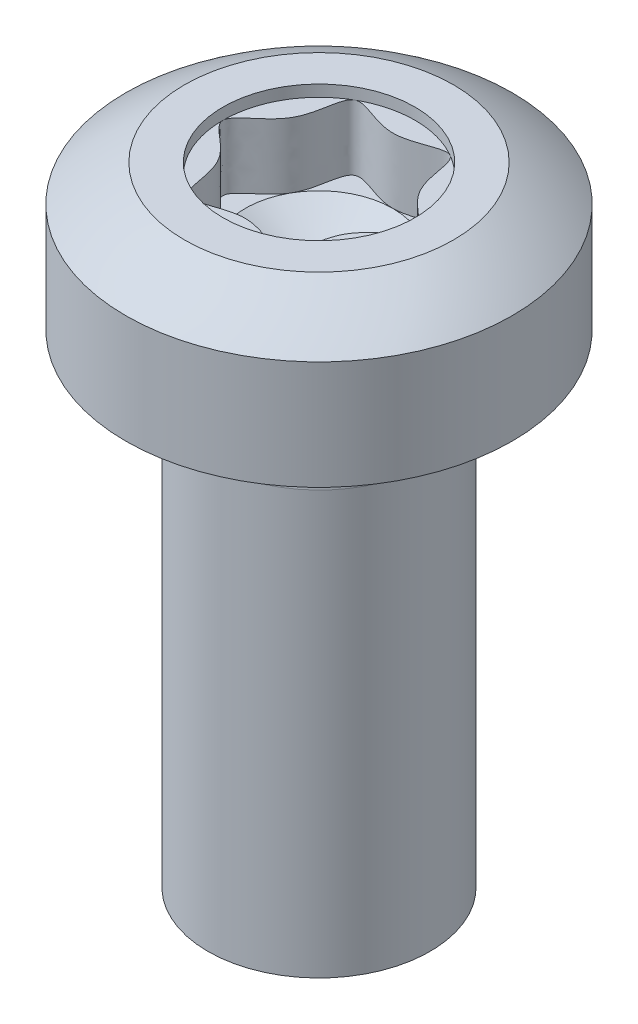
SolidWorks part; units mm, degrees
ref_plane "Front" through (0, 0, 0) normal (0, 0, 1) x (1, 0, 0)
ref_plane "Top" through (0, 0, 0) normal (0, 1, 0) x (1, 0, 0)
ref_plane "Right" through (0, 0, 0) normal (1, 0, 0) x (0, 0, -1)
sketch "Sketch1" plane through (0, 0, 0) normal (0, 0, 1) x (1, 0, 0)
  line L0 (0, 0) -> (0, 34.6184) construction
  line L1 (0, 0) -> (4.6, 0)
  line L2 (4.6, 0) -> (4.6, 20)
  line L3 (4.6, 20) -> (8, 20)
  line L4 (8, 20) -> (8, 26)
  line L5 (8, 26) -> (0, 26)
  line L6 (0, 26) -> (0, 0)
  line L7 (8, 20) -> (9.25, 20) construction
  line L8 (9.25, 20) -> (9.25, 2.5) construction
  dimension "HEAD_DIA" = 16
  dimension "HEAD_HT" = 6
  dimension "LENGTH" = 20
  dimension "DIA" = 9.2
  dimension "pitch" = 1.25
  dimension "thread_length" = 17.5
revolve "BODY" add sketch "Sketch1" angle 360 about L0
cosmetic thread "ThreadCosmetic" parameters "D1"=17.5, "D2"=7.8469
sketch "Sketch2" plane through (0, 0, 0) normal (0, 0, 1) x (1, 0, 0)
  line L0 (8, 24.5) -> (0, 14.253) construction
  line L3 (8, 20) -> (8, 26) construction
  line L4 (0, 0) -> (0, 34.6184) construction
  line L5 (0, 27.253) -> (0, 27.7352)
  line L6 (13, 14.253) -> (13, 27.7352)
  line L7 (13, 27.7352) -> (0, 27.7352)
  line L8 (0, 27.7352) -> (13, 27.7352)
  arc A0 (13, 14.253) -> (0, 27.253) centre (0, 14.253) ccw
  dimension "SPHERE_DIA" = 13
  dimension "D1" = 1.5
  dimension "D2" = 0.4822
revolve "HEAD-CUT" cut sketch "Sketch2" angle 360 about axis through (0, 0, 0) along (0, 1, 0)
sketch "Sketch4" plane through (0, 0, 0) normal (0, 0, 1) x (1, 0, 0)
  line L0 (-4.6, 17.5) -> (-4.38, 19.6)
  line L1 (-4.6, 20) -> (-4.6, 0) construction
  line L2 (-4.6, 20) -> (-4.6, 17.5)
  arc A0 (-4.38, 19.6) -> (-4.6, 20) centre (-4.7778, 19.6417) ccw
  dimension "CONER_RAD" = 0.4
  dimension "D1" = 0.4
  dimension "GAP" = 2.5
revolve "GAP" cut sketch "Sketch4" angle 360 about axis through (0, 0, 0) along (0, 1, 0)
sketch "Sketch5" plane through (0, 26, 0) normal (0, 1, 0) x (-1, 0, 0)
  line L0 (0, 3.0577) -> (0, 0) construction
  line L1 (0, 0) -> (1.9875, 3.4425) construction
  line L2 (1.9875, 3.4425) -> (-1.9875, 3.4425) construction
  line L3 (-1.9875, 3.4425) -> (-3.975, 0) construction
  line L4 (-3.975, 0) -> (-1.9875, -3.4425) construction
  line L5 (-1.9875, -3.4425) -> (1.9875, -3.4425) construction
  line L6 (1.9875, -3.4425) -> (3.975, 0) construction
  line L7 (3.975, 0) -> (1.9875, 3.4425) construction
  line L8 (0, 3.0577) -> (-2.648, 1.5288) construction
  line L9 (-2.648, 1.5288) -> (-2.648, -1.5288) construction
  line L10 (-2.648, -1.5288) -> (0, -3.0577) construction
  line L11 (0, -3.0577) -> (2.648, -1.5288) construction
  line L12 (2.648, -1.5288) -> (2.648, 1.5288) construction
  line L13 (2.648, 1.5288) -> (0, 3.0577) construction
  circle A0 centre (0, 0) radius 3.0577 construction
  circle A1 centre (0, 0) radius 3.975
  spline S0 degree 3 poles (2.4471, 4.2384) (0, 2.4673) (-2.4471, 4.2384) (-2.1368, 1.2337) (-4.8941, 0) (-2.1368, -1.2337) (-2.4471, -4.2384) (0, -2.4673) (2.4471, -4.2384) (2.1368, -1.2337) (4.8941, 0) (2.1368, 1.2337) (2.4471, 4.2384) (0, 2.4673) (-2.4471, 4.2384) knots -0.25 -0.166667 -0.083333 0 0.083333 0.166667 0.25 0.333333 0.416667 0.5 0.583333 0.666667 0.75 0.833333 0.916667 1 1.083333 1.166667 1.25 only from (0, 3.0577) to (0, 3.0577)
  dimension "slot_dia" = 7.95
  dimension "D3" = 6.1154
  dimension "D1" = 30
extrude "Recess-Cut-Extrude1" cut sketch "Sketch5" against normal blind 3.18
sketch "Sketch3" plane through (0, 0, 0) normal (0, 0, 1) x (1, 0, 0)
  line L0 (0, 21.0546) -> (3.0577, 22.82)
  line L1 (0, 0) -> (0, 34.6184) construction
  line L2 (3.0577, 22.82) -> (0, 22.82)
  line L3 (0, 22.82) -> (0, 21.0546)
  dimension "D1" = 60
  dimension "DRILL_RAD" = 3.0577
  dimension "SLOT_DEP" = 3.18
revolve "DRILL-CUT" cut sketch "Sketch3" angle 360 about axis through (0, 0, 0) along (0, 1, 0)
sketch "Sketch6" plane through (0, 0, 0) normal (0, 0, 1) x (1, 0, 0)
  line L0 (4.6, 0) -> (3.9234, 0.3906)
  line L1 (3.9234, 0.3906) -> (4.6, 0.7812)
  line L4 (4.6, 0.7812) -> (4.6, 0)
  line L5 (0, 0) -> (0, 34.6184) construction
  dimension "D1" = 3.9234
revolve "ThreadSchematic" [suppressed] cut sketch "Sketch6" angle 360 about axis through (0, 0, 0) along (0, 1, 0)
pattern_linear "ThdSchPat" [suppressed] count 14 spacing 1.25 along (0, 1, 0)
sketch "Sketch7" plane through (0, 26, 0) normal (0, 1, 0) x (-1, 0, 0)
  circle A0 centre (0, 0) radius 3.975
  dimension "D1" = 7.95
extrude "Recess-Cut-Extrude2" cut sketch "Sketch7" against normal blind 0.477
equation "\"D1@Sketch2\" = \"HEAD_HT@Sketch1\" * 0.25"
equation "\"D1@Sketch4\" = \"CONER_RAD@Sketch4\""
equation "\"D1@Recess-Cut-Extrude1\" = \"SLOT_DEP@Sketch3\""
equation "\"D1@Sketch7\" = \"slot_dia@Sketch5\""
equation "\"D1@Recess-Cut-Extrude2\" = \"SLOT_DEP@Sketch3\" * 0.15"
equation "\"D3@Sketch5\" = \"slot_dia@Sketch5\" / 1.3"
equation "\"DRILL_RAD@Sketch3\" = \"D3@Sketch5\" * 0.5"
equation "\"D1@ThreadCosmetic\" = \"thread_length@Sketch1\""
equation "\"D2@ThreadCosmetic\" = \"DIA@Sketch1\" - 1.0825 * \"pitch@Sketch1\""
equation "\"D1@Sketch6\" = \"D2@ThreadCosmetic\" / 2"
equation "\"D3@ThdSchPat\" = \"pitch@Sketch1\""
equation "\"D1@ThdSchPat\" = \"thread_length@Sketch1\" / \"pitch@Sketch1\""
